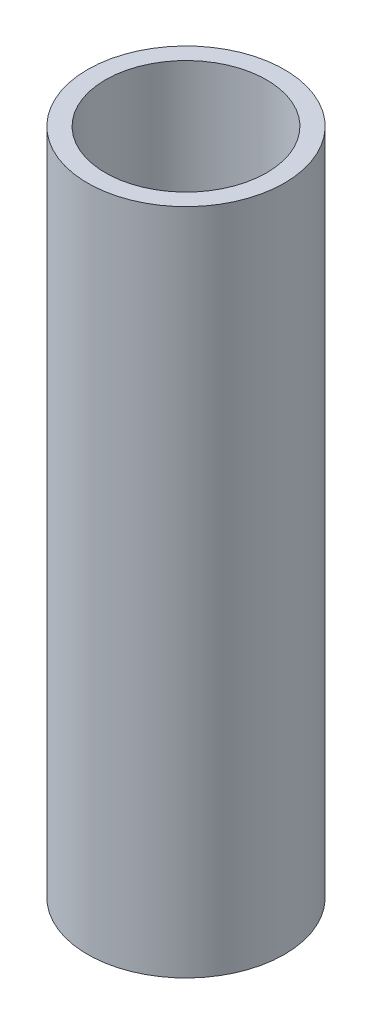
SolidWorks part; units mm, degrees
material "AISI 316 Stainless Steel Sheet (SS)"
ref_plane "Front Plane" through (0, 0, 0) normal (0, 0, 1) x (1, 0, 0)
ref_plane "Top Plane" through (0, 0, 0) normal (0, 1, 0) x (1, 0, 0)
ref_plane "Right Plane" through (0, 0, 0) normal (1, 0, 0) x (0, 0, -1)
sketch "Sketch1" plane through (0, 33.8556, 0) normal (0, -1, 0) x (1, 0, 0)
  circle A0 centre (0.7, -1.6) radius 0.7366
  circle A1 centre (0.7, -1.6) radius 0.6033
  dimension "D1" = 1.4732
  dimension "D2" = 1.2065
extrude "Boss-Extrude1" add sketch "Sketch1" along normal up to surface (5 mm away)
